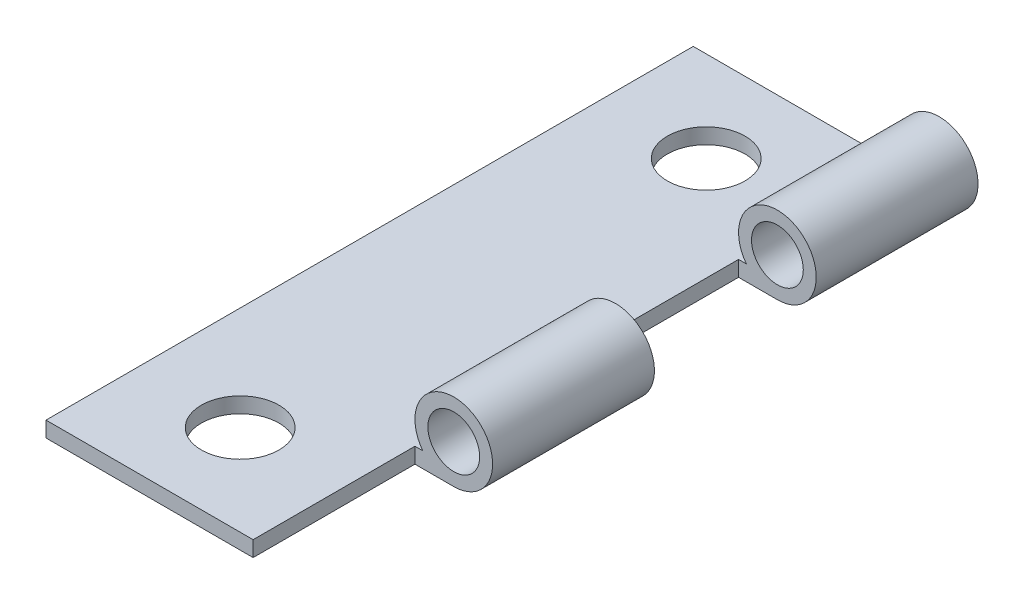
SolidWorks part; units mm, degrees
ref_plane "前视基准面" through (0, 0, 0) normal (0, 0, 1) x (1, 0, 0)
ref_plane "上视基准面" through (0, 0, 0) normal (0, 1, 0) x (1, 0, 0)
ref_plane "右视基准面" through (0, 0, 0) normal (1, 0, 0) x (0, 0, -1)
sketch "草图2" plane through (0, 0, 0) normal (0, 0, 1) x (1, 0, 0)
  line L7 (0, -1.5) -> (-9.5, -1.5)
  line L8 (-9.5, -1.5) -> (-9.5, -0.9)
  line L9 (-9.5, -0.9) -> (-1.2, -0.9)
  circle A4 centre (0, 0) radius 1
  arc A5 (0, -1.5) -> (-1.2, -0.9) centre (0, 0) ccw
  dimension "D1" = 2
  dimension "D2" = 3
  dimension "D3" = 9.5
  dimension "D4" = 0.6
extrude "凸台-拉伸1" add sketch "草图2" along normal mid plane 25
sketch "草图3" plane through (0, -0.9, 0) normal (0, 1, 0) x (1, 0, 0)
  line L1 (-1.5, 6.25) -> (2.5999, 6.25)
  line L2 (-1.5, 6.25) -> (-1.5, 0)
  line L3 (-1.5, 0) -> (2.5999, 0)
  line L4 (2.5999, 6.25) -> (2.5999, 0)
  line L6 (-1.5, -6.25) -> (3.186, -6.25)
  line L7 (-1.5, -6.25) -> (-1.5, -12.5)
  line L8 (-1.5, -12.5) -> (3.186, -12.5)
  line L9 (3.186, -6.25) -> (3.186, -12.5)
  line L10 (-1.5, -12.5) -> (1.5, -12.5) construction
  dimension "D1" = 6.25
  dimension "D2" = 0
  dimension "D3" = 6.25
extrude "切除-拉伸1" cut sketch "草图3" against normal mid plane 20 contours L6 L9 L8 L7 | L2 L1 L4 L3
sketch "草图4" plane through (0, -0.9, 0) normal (0, 1, 0) x (1, 0, 0)
  line L0 (-5.5, 9) -> (-5.5, -9) construction
  line L2 (-1.5, -12.5) -> (-9.5, -12.5) construction
  circle A0 centre (-5.5, 9) radius 1.5
  circle A1 centre (-5.5, -9) radius 1.5
  dimension "D1" = 3
  dimension "D2" = 3
  dimension "D3" = 5.5
  dimension "D4" = 18
  dimension "D5" = 3.5
extrude "切除-拉伸2" cut sketch "草图4" against normal blind 10
